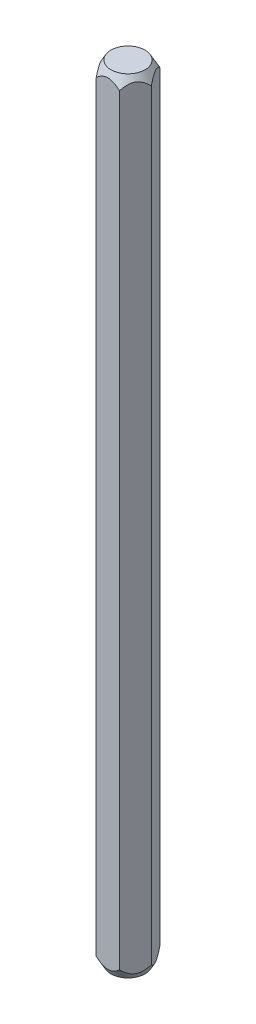
SolidWorks part; units mm, degrees
ref_plane "Front Plane" through (0, 0, 0) normal (0, 0, 1) x (1, 0, 0)
ref_plane "Top Plane" through (0, 0, 0) normal (0, 1, 0) x (1, 0, 0)
ref_plane "Right Plane" through (0, 0, 0) normal (1, 0, 0) x (0, 0, -1)
sketch "Sketch1" plane through (0, 0, 0) normal (0, 1, 0) x (1, 0, 0)
  line L0 (0, 0) -> (1.5, 0) construction
  line L7 (1.5, 0) -> (0.75, 1.299)
  line L8 (0.75, 1.299) -> (-0.75, 1.299)
  line L9 (-0.75, 1.299) -> (-1.5, 0)
  line L10 (-1.5, 0) -> (-0.75, -1.299)
  line L11 (-0.75, -1.299) -> (0.75, -1.299)
  line L12 (0.75, -1.299) -> (1.5, 0)
  circle A0 centre (0, 0) radius 1.5 construction
  dimension "D1" = 3
extrude "Boss-Extrude1" add sketch "Sketch1" along normal mid plane 50.5
sketch3d "3DSketch1"
  line L0 (0, -25.25, 0) -> (0, 25.25, 0)
  line L1 (1.5, 25.25, 0) -> (-1.5, 25.25, 0) construction
  line L2 (1.5, -25.25, 0) -> (-1.5, -25.25, 0) construction
  point P13 (0, -25.25, 0)
  point P14 (0, 25.25, 0)
sketch "Sketch2" plane through (0, 0, 0) normal (0, 0, 1) x (1, 0, 0)
  line L0 (1.5, 25.25) -> (1.5, 24.55)
  line L1 (1.5, 25.25) -> (1.5, -25.25) construction
  line L2 (1.5, 24.55) -> (1.1, 25.25)
  line L3 (1.1, 25.25) -> (1.5, 25.25)
  line L4 (1.5, -25.25) -> (1.5, -24.55)
  line L5 (1.5, -24.55) -> (1.1, -25.25)
  line L6 (1.1, -25.25) -> (1.5, -25.25)
  dimension "D1" = 0.7
  dimension "D2" = 0.4
revolve "Cut-Revolve1" cut sketch "Sketch2" angle 360 about L0
